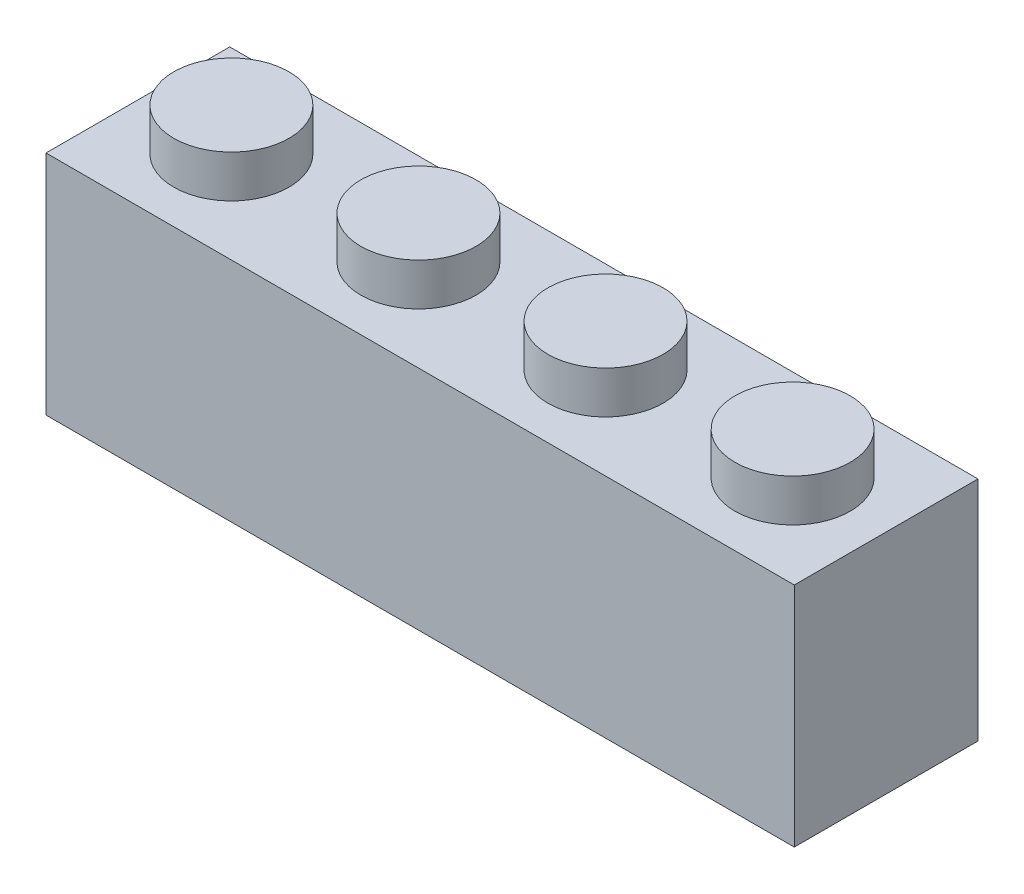
SolidWorks part; units mm, degrees
ref_plane "Front Plane" through (0, 0, 0) normal (0, 0, 1) x (1, 0, 0)
ref_plane "Top Plane" through (0, 0, 0) normal (0, 1, 0) x (1, 0, 0)
ref_plane "Right Plane" through (0, 0, 0) normal (1, 0, 0) x (0, 0, -1)
sketch "Sketch2" plane through (0, 0, 0) normal (0, 1, 0) x (1, 0, 0)
  line L1 (-15.905, 3.905) -> (15.905, 3.905)
  line L2 (-15.905, 3.905) -> (-15.905, -3.905)
  line L3 (-15.905, -3.905) -> (15.905, -3.905)
  line L4 (15.905, 3.905) -> (15.905, -3.905)
  line L5 (-15.905, 3.905) -> (15.905, -3.905) construction
  line L6 (-15.905, -3.905) -> (15.905, 3.905) construction
  point P0 (0, 0)
  dimension "D1" = 7.81
  dimension "D2" = 31.81
extrude "Boss-Extrude1" add sketch "Sketch2" against normal blind 9.65
sketch "Sketch3" plane through (0, 0, 0) normal (0, 1, 0) x (1, 0, 0)
  line L0 (15.905, 3.905) -> (-15.905, 3.905) construction
  line L2 (-15.905, 3.905) -> (-15.905, -3.905) construction
  circle A0 centre (-11.9287, 0) radius 2.45
  circle A1 centre (-3.9762, 0) radius 2.45
  circle A2 centre (3.9763, 0) radius 2.45
  circle A3 centre (11.9288, 0) radius 2.45
  dimension "D1" = 4.9
  dimension "D5" = 7.9525
  dimension "D2" = 3.905
  dimension "D3" = 3.9762
  dimension "D4" = 4
extrude "Boss-Extrude2" add sketch "Sketch3" along normal blind 1.8
shell "Shell1" thickness 1.5
sketch "Sketch4" plane through (0, -1.5, 0) normal (0, -1, 0) x (1, 0, 0)
  line L1 (-15.905, -3.905) -> (-15.905, 3.905) construction
  line L2 (15.905, -3.905) -> (-15.905, -3.905) construction
  circle A0 centre (-7.9525, 0) radius 1.5
  circle A1 centre (0, 0) radius 1.5
  circle A2 centre (7.9525, 0) radius 1.5
  dimension "D1" = 3
  dimension "D2" = 7.9525
  dimension "D5" = 7.9525
  dimension "D3" = 3.905
  dimension "D4" = 3
extrude "Boss-Extrude3" add sketch "Sketch4" along normal offset from surface (7.95 mm away) 0.2 up to face at (0, -9.65, 0)
